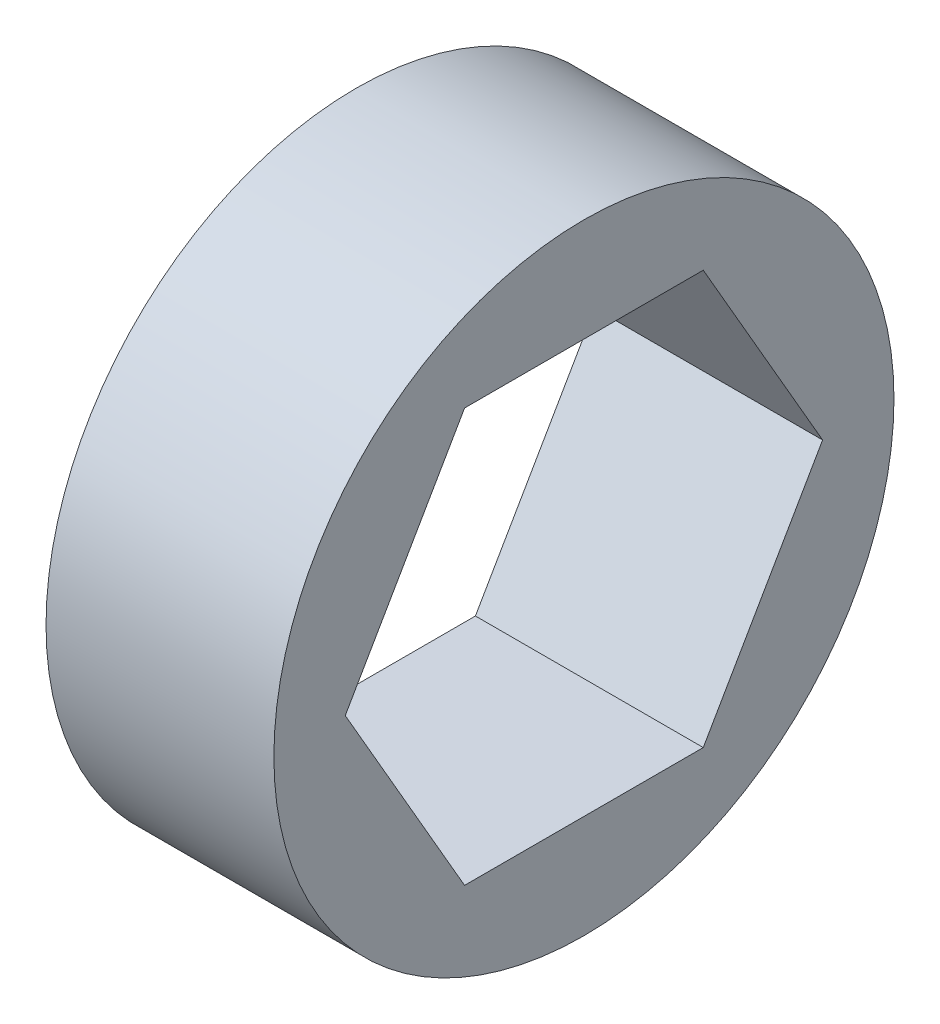
SolidWorks part; units mm, degrees
material "POM Acetal Copolymer"
ref_plane "Front Plane" through (0, 0, 0) normal (0, 0, 1) x (1, 0, 0)
ref_plane "Top Plane" through (0, 0, 0) normal (0, 1, 0) x (1, 0, 0)
ref_plane "Right Plane" through (0, 0, 0) normal (1, 0, 0) x (0, 0, -1)
sketch "Sketch1" plane through (0, 0, 0) normal (1, 0, 0) x (0, 0, -1)
  line L1 (7.3323, 0) -> (3.6662, 6.35)
  line L2 (3.6662, 6.35) -> (-3.6662, 6.35)
  line L3 (-3.6662, 6.35) -> (-7.3323, 0)
  line L4 (-7.3323, 0) -> (-3.6662, -6.35)
  line L5 (-3.6662, -6.35) -> (3.6662, -6.35)
  line L6 (3.6662, -6.35) -> (7.3323, 0)
  circle A0 centre (0, 0) radius 6.35 construction
  circle A1 centre (0, 0) radius 9.525
  dimension "D1" = 12.7
  dimension "D2" = 3.175
extrude "Boss-Extrude1" add sketch "Sketch1" along normal mid plane 7
